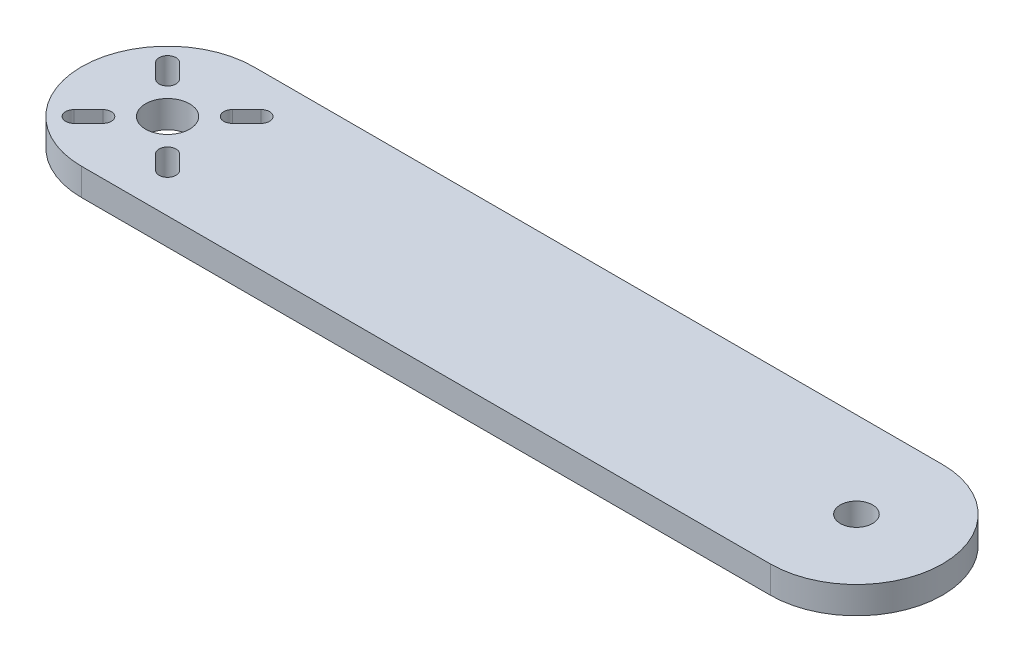
SolidWorks part; units mm, degrees
material "Thornel VCB-20 Carbon Cloth"
ref_plane "Front Plane" through (0, 0, 0) normal (0, 0, 1) x (1, 0, 0)
ref_plane "Top Plane" through (0, 0, 0) normal (0, 1, 0) x (1, 0, 0)
ref_plane "Right Plane" through (0, 0, 0) normal (1, 0, 0) x (0, 0, -1)
sketch "Sketch1" plane through (0, 0, 0) normal (0, 1, 0) x (1, 0, 0)
  line L0 (-58.0134, 7.2134) -> (-43.5866, -7.2134) construction
  line L1 (-50.8, 12.7) -> (50.8, 12.7)
  line L2 (-50.8, 12.7) -> (-50.8, -12.7) construction
  line L3 (-50.8, -12.7) -> (50.8, -12.7)
  line L4 (50.8, 12.7) -> (50.8, -12.7) construction
  line L5 (-50.8, 12.7) -> (50.8, -12.7) construction
  line L6 (-50.8, -12.7) -> (50.8, 12.7) construction
  line L7 (-58.4887, -7.6887) -> (-43.1113, 7.6887) construction
  line L8 (-57.6943, 6.8943) -> (-55.573, 4.773) construction
  line L9 (-56.8104, 7.7782) -> (-54.6891, 5.6569)
  line L10 (-58.5782, 6.0104) -> (-56.4569, 3.8891)
  line L11 (-43.9057, 6.8943) -> (-46.027, 4.773) construction
  line L12 (-43.0218, 6.0104) -> (-45.1431, 3.8891)
  line L13 (-44.7896, 7.7782) -> (-46.9109, 5.6569)
  line L14 (-43.9057, -6.8943) -> (-46.027, -4.773) construction
  line L15 (-44.7896, -7.7782) -> (-46.9109, -5.6569)
  line L16 (-43.0218, -6.0104) -> (-45.1431, -3.8891)
  line L17 (-57.6943, -6.8943) -> (-55.573, -4.773) construction
  line L18 (-58.5782, -6.0104) -> (-56.4569, -3.8891)
  line L19 (-56.8104, -7.7782) -> (-54.6891, -5.6569)
  arc A0 (-50.8, 12.7) -> (-50.8, -12.7) centre (-50.8, 0) ccw
  arc A1 (50.8, -12.7) -> (50.8, 12.7) centre (50.8, 0) ccw
  circle A2 centre (-50.8, 0) radius 3.25
  arc A3 (-56.8104, 7.7782) -> (-58.5782, 6.0104) centre (-57.6943, 6.8943) ccw
  arc A4 (-56.4569, 3.8891) -> (-54.6891, 5.6569) centre (-55.573, 4.773) ccw
  arc A5 (-43.0218, 6.0104) -> (-44.7896, 7.7782) centre (-43.9057, 6.8943) ccw
  arc A6 (-46.9109, 5.6569) -> (-45.1431, 3.8891) centre (-46.027, 4.773) ccw
  arc A7 (-44.7896, -7.7782) -> (-43.0218, -6.0104) centre (-43.9057, -6.8943) ccw
  arc A8 (-45.1431, -3.8891) -> (-46.9109, -5.6569) centre (-46.027, -4.773) ccw
  arc A9 (-58.5782, -6.0104) -> (-56.8104, -7.7782) centre (-57.6943, -6.8943) ccw
  arc A10 (-54.6891, -5.6569) -> (-56.4569, -3.8891) centre (-55.573, -4.773) ccw
  circle A11 centre (50.8, 0) radius 2.3812
  point P0 (0, 0)
  point P12 (-50.8, 0)
  point P14 (-50.8, 0)
  point P17 (-56.6336, 5.8336)
  point P27 (-44.9664, 5.8336)
  point P34 (-44.9664, -5.8336)
  point P41 (-56.6336, -5.8336)
  point P46 (-50.8, 0)
  dimension "D3" = 6.5
  dimension "D6" = 8.25
  dimension "D10" = 4.7625
  dimension "D1" = 101.6
  dimension "D2" = 25.4
  dimension "D4" = 45
  dimension "D5" = 45
  dimension "D7" = 3
  dimension "D8" = 2.5
  dimension "D9" = 4
extrude "Boss-Extrude1" add sketch "Sketch1" along normal blind 4
